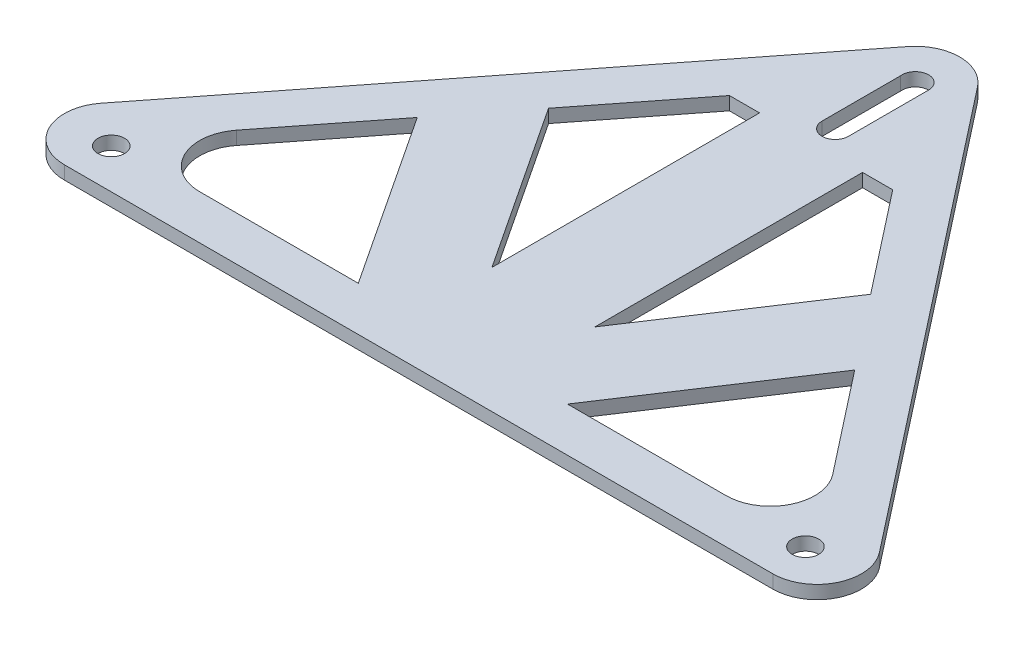
SolidWorks part; units mm, degrees
ref_plane "Front Plane" through (0, 0, 0) normal (0, 0, 1) x (1, 0, 0)
ref_plane "Top Plane" through (0, 0, 0) normal (0, 1, 0) x (1, 0, 0)
ref_plane "Right Plane" through (0, 0, 0) normal (1, 0, 0) x (0, 0, -1)
sketch "Sketch1" plane through (0, 0, 0) normal (0, 1, 0) x (1, 0, 0)
  line L1 (11.0372, 17.1903) -> (28.9594, 40.0777)
  line L2 (166.1061, 7.1903) -> (86.1791, 109.2606)
  line L5 (-9.4945, 7.1903) -> (70.4325, 109.2606)
  line L6 (-1.6212, -8.975) -> (158.2327, -8.975)
  line L8 (18.9105, 1.025) -> (54.7068, 1.025)
  line L9 (-1.6212, 1.025) -> (158.2327, 1.025) construction
  line L10 (78.3058, 103.0953) -> (78.3058, 85.0301) construction
  line L11 (81.2843, 103.0953) -> (81.2843, 85.0301)
  line L12 (75.3272, 103.0953) -> (75.3272, 85.0301)
  line L13 (158.2327, 1.025) -> (78.3058, 103.0953) construction
  line L14 (-1.6212, 1.025) -> (78.3058, 103.0953) construction
  line L17 (78.3058, 85.0301) -> (78.3058, -8.975)
  line L18 (89.9269, 19.1924) -> (114.6467, 56.6863)
  line L19 (101.9047, 1.025) -> (127.6522, 40.0777)
  line L20 (137.7011, 1.025) -> (101.9047, 1.025)
  line L21 (89.9269, 79.5737) -> (89.9269, 19.1924)
  line L22 (66.6846, 79.5737) -> (66.6846, 19.1924)
  line L23 (89.9269, 79.5737) -> (96.7245, 79.5737)
  line L24 (145.5744, 17.1903) -> (127.6522, 40.0777)
  line L25 (41.9649, 56.6863) -> (59.887, 79.5737)
  line L26 (66.6846, 79.5737) -> (59.887, 79.5737)
  line L27 (11.0372, 17.1903) -> (59.887, 79.5737) construction
  line L28 (66.6846, 79.5737) -> (66.6846, 1.025) construction
  line L32 (66.6846, 79.5737) -> (66.6846, 66.3647)
  line L33 (66.6846, 19.1924) -> (41.9649, 56.6863)
  line L34 (54.7068, 1.025) -> (28.9594, 40.0777)
  line L35 (18.9105, 1.025) -> (66.6846, 1.025) construction
  line L36 (60.6846, 70.8603) -> (60.6846, 70.8603)
  line L37 (114.6467, 56.6863) -> (96.7245, 79.5737)
  line L40 (60.6846, 70.8603) -> (60.6846, 7.025) construction
  line L48 (15.7612, 13.4911) -> (60.6846, 70.8603) construction
  line L49 (18.9105, 7.025) -> (60.6846, 7.025) construction
  arc A3 (-9.4945, 7.1903) -> (-1.6212, -8.975) centre (-1.6212, 1.025) ccw
  arc A4 (166.1061, 7.1903) -> (158.2327, -8.975) centre (158.2327, 1.025) cw
  arc A5 (86.1791, 109.2606) -> (70.4325, 109.2606) centre (78.3058, 103.0953) ccw
  circle A6 centre (78.3058, 103.0953) radius 3
  circle A7 centre (156.6116, 0) radius 3
  circle A8 centre (0, 0) radius 3
  arc A9 (81.2843, 103.0953) -> (75.3272, 103.0953) centre (78.3058, 103.0953) ccw
  arc A10 (75.3272, 85.0301) -> (81.2843, 85.0301) centre (78.3058, 85.0301) ccw
  arc A15 (158.2327, 1.025) -> (158.2327, 1.025) centre (158.2327, 1.025) cw construction
  arc A17 (78.3058, 103.0953) -> (78.3058, 103.0953) centre (78.3058, 103.0953) ccw construction
  arc A18 (18.9105, 1.025) -> (11.0372, 17.1903) centre (18.9105, 11.025) cw
  arc A19 (-1.6212, 1.025) -> (-1.6212, 1.025) centre (-1.6212, 1.025) ccw construction
  arc A21 (18.9105, 7.025) -> (15.7612, 13.4911) centre (18.9105, 11.025) cw construction
  arc A22 (137.7011, 1.025) -> (145.5744, 17.1903) centre (137.7011, 11.025) ccw
  point P23 (78.3058, 94.0627)
  dimension "D1" = 10
  dimension "D2" = 10
extrude "Boss-Extrude1" add sketch "Sketch1" along normal blind 3
